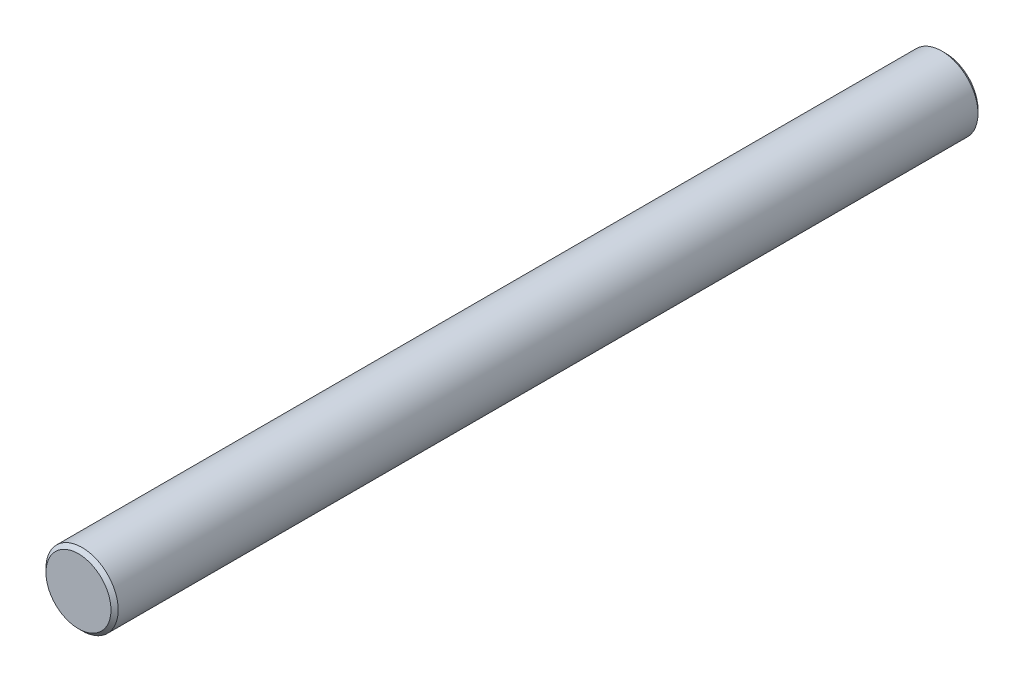
SolidWorks part; units mm, degrees
ref_plane "Front Plane" through (0, 0, 0) normal (0, 0, 1) x (1, 0, 0)
ref_plane "Top Plane" through (0, 0, 0) normal (0, 1, 0) x (1, 0, 0)
ref_plane "Right Plane" through (0, 0, 0) normal (1, 0, 0) x (0, 0, -1)
sketch "Sketch1" plane through (0, 0, 0) normal (0, 0, 1) x (1, 0, 0)
  circle A0 centre (0, 0) radius 5
  dimension "D1" = 10
extrude "Boss-Extrude1" add sketch "Sketch1" along normal mid plane 120
chamfer "Chamfer1" distance 0.5 angle 45 2 edges at (5, 0, -60) (5, 0, 60)
